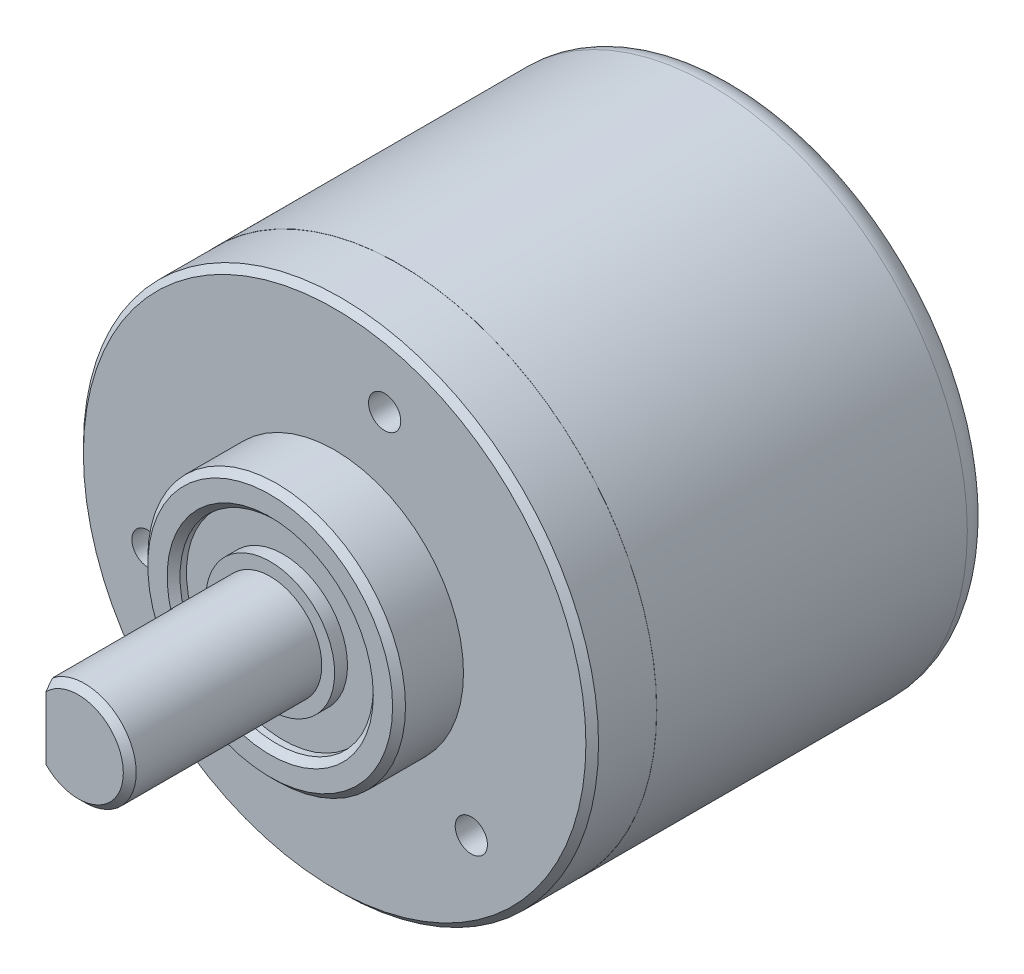
SolidWorks part; units mm, degrees
ref_plane "Frente" through (0, 0, 0) normal (0, 0, 1) x (1, 0, 0)
ref_plane "Topo" through (0, 0, 0) normal (0, 1, 0) x (1, 0, 0)
ref_plane "Lateral" through (0, 0, 0) normal (1, 0, 0) x (0, 0, -1)
ref_plane "Plane1" [suppressed] through (-13, 0, 0) normal (-1, 0, 0) x (0, 1, 0)
sketch "Sketch37" plane through (0, 0, 0) normal (1, 0, 0) x (0, 0, -1)
  line L0 (0, 0) -> (72.3545, 0) construction
  line L1 (0, 0) -> (0, -4)
  line L2 (0, -4) -> (14.9, -4)
  line L3 (14.9, -4) -> (14.9, -5)
  line L4 (14.9, -5) -> (15.9, -5)
  line L5 (15.9, -5) -> (15.9, -7.5)
  line L6 (15.9, -7.5) -> (14.9, -7.5)
  line L7 (14.9, -7.5) -> (14.9, -10)
  line L8 (14.9, -10) -> (19.9, -10)
  line L9 (19.9, -10) -> (19.9, -20)
  line L10 (19.9, -20) -> (51, -20)
  line L11 (51, -20) -> (51, 0)
  line L12 (0, 0) -> (51, 0)
  dimension "D1" = 8
  dimension "D2" = 20
  dimension "D3" = 10
  dimension "D4" = 15
  dimension "D5" = 40
  dimension "D6" = 14.9
  dimension "D7" = 1
  dimension "D8" = 5
  dimension "D9" = 51
revolve "Revolve3" add sketch "Sketch37" angle 360 about L0
fillet "Fillet3" radius 2 1 edges at (20, 0, -51)
sketch "Sketch38" plane through (0, 0, 0) normal (0, 0, 1) x (1, 0, 0)
  line L0 (-2.5, 3.1225) -> (-2.5, -3.1225)
  circle A0 centre (0, 0) radius 4 construction
  arc A1 (-2.5, 3.1225) -> (-2.5, -3.1225) centre (0, 0) ccw
  dimension "D1" = 2.5
extrude "Cut-Extrude11" cut sketch "Sketch38" against normal blind 10
chamfer "Chamfer6" distance 0.5 angle 45 4 edges at (7.5, 0, -14.9) (4, 0, 0) (10, 0, -14.9) (20, 0, -19.9)
hole_wizard "M3x0.5 Tapped Hole1" positions "Sketch41" profile "Sketch40" tap size "M3x0.5" standard "DIN"
sketch "Sketch41" plane through (0, 0, -19.9) normal (0, 0, 1) x (1, 0, 0)
  line L0 (0, 0) -> (0, -14) construction
  line L1 (0, 0) -> (10.6066, -10.6066) construction
  circle A0 centre (0, 0) radius 14 construction
  circle A1 centre (0, 0) radius 15 construction
  point P0 (0, -14)
  point P6 (10.6066, -10.6066)
  dimension "D1" = 28
  dimension "D2" = 30
  dimension "D3" = 45
sketch "Sketch40" plane through (0, -14, -19.9) normal (1, 0, 0) x (0, -1, 0)
  line L0 (0, 0) -> (0, 9.2511)
  line L1 (0, 9.2511) -> (1.25, 8.5)
  line L2 (1.25, 8.5) -> (1.25, 0)
  line L5 (1.25, 0) -> (0, 0)
  line L10 (0, 9.2511) -> (-1.25, 8.5) construction
  line L11 (0, -6.35) -> (0, 107.95) construction
  dimension "Tap Drill Dia." = 2.5
  dimension "Tap Drill Depth" = 8.5
  dimension "Drill Angle" = 118
cosmetic thread "Hole Thread3" parameters "D1"=6, "D2"=3
cosmetic thread "Hole Thread4" parameters "D1"=6, "D2"=3
pattern_circular "CirPattern4" count 3 over 360 about axis through (0, 0, 0) along (0, 0, 1) of "M3x0.5 Tapped Hole1"
sketch "Sketch43" plane through (0, 0, -19.9) normal (0, 0, 1) x (1, 0, 0)
  circle A0 centre (0, -14) radius 1.25 construction
  circle A1 centre (0, -14) radius 1.25
  circle A2 centre (-12.1244, 7) radius 1.25 construction
  circle A3 centre (-12.1244, 7) radius 1.25
  circle A4 centre (12.1244, 7) radius 1.25 construction
  circle A5 centre (12.1244, 7) radius 1.25
extrude "Extrude13" add sketch "Sketch43" against normal blind 15
sketch "Sketch44" plane through (0, 0, -19.9) normal (0, 0, 1) x (1, 0, 0)
  circle A0 centre (0, 0) radius 20 construction
  circle A1 centre (0, 0) radius 20
  circle A2 centre (0, 0) radius 19.99
  dimension "D1" = 0.01
extrude "Cut-Extrude13" cut sketch "Sketch44" against normal blind 5
ref_plane "Plane2" through (0, 20, -36.95) normal (0, 1, 0) x (-1, 0, 0)
sketch "Sketch45" plane through (0, 0, -51) normal (0, 0, -1) x (-1, 0, 0)
  circle A0 centre (0, 0) radius 5
  dimension "D1" = 10
